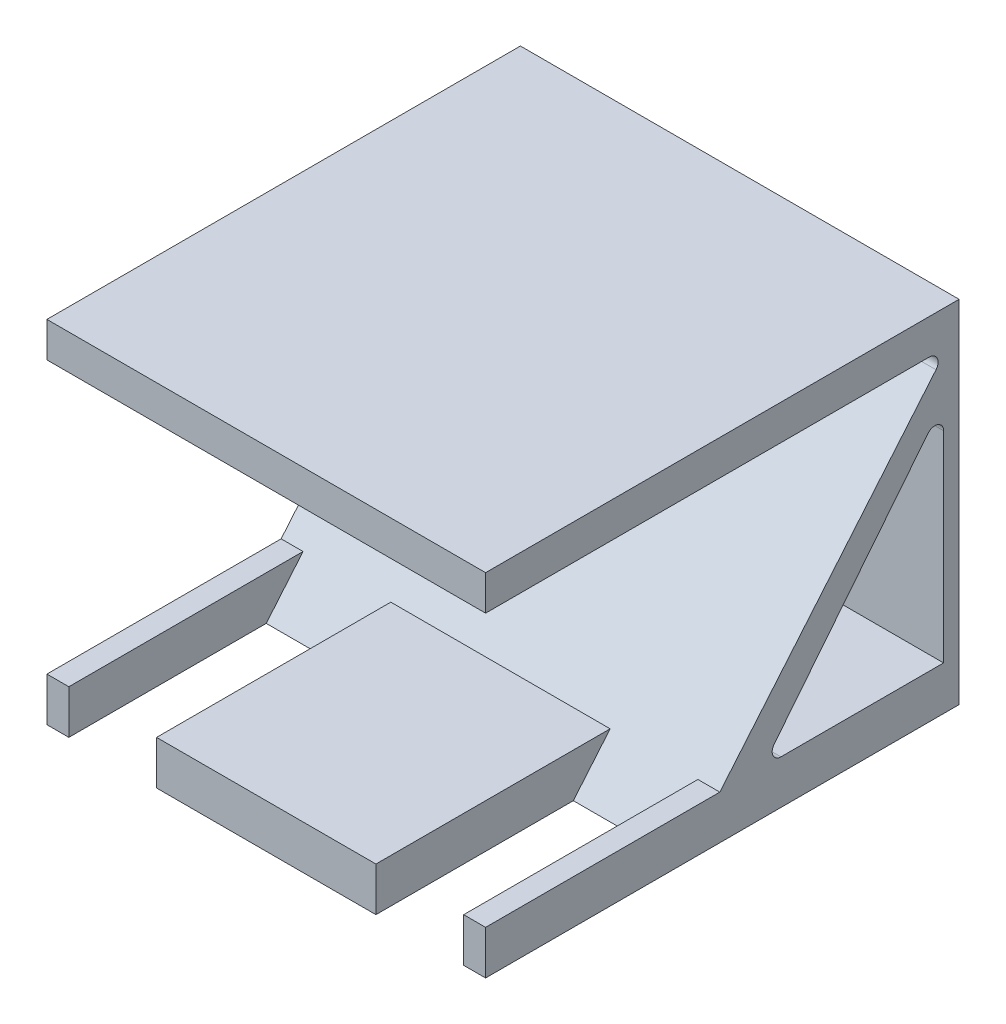
SolidWorks part; units mm, degrees
ref_plane "前视基准面" through (0, 0, 0) normal (0, 0, 1) x (1, 0, 0)
ref_plane "上视基准面" through (0, 0, 0) normal (0, 1, 0) x (1, 0, 0)
ref_plane "右视基准面" through (0, 0, 0) normal (1, 0, 0) x (0, 0, -1)
other "Configuration Table"
sketch "草图2" plane through (0, 0, 0) normal (0, 1, 0) x (1, 0, 0)
  line L0 (0, 45) -> (0, -64.4756) construction
  line L1 (-50, -45) -> (50, -45)
  line L2 (-50, -45) -> (-50, 45)
  line L3 (-50, 45) -> (50, 45)
  line L4 (50, -45) -> (50, 45)
  line L5 (-50, -45) -> (50, 45) construction
  line L6 (-50, 45) -> (50, -45) construction
  line L7 (-45, 45) -> (-25, 45)
  line L8 (-45, 45) -> (-45, -45)
  line L9 (-45, -45) -> (-25, -45)
  line L10 (-25, 45) -> (-25, -45)
  line L11 (45, -45) -> (25, -45)
  line L12 (25, 45) -> (25, -45)
  line L13 (45, 45) -> (25, 45)
  line L14 (45, 45) -> (45, -45)
  point P0 (0, 0)
  dimension "D1" = 100
  dimension "D2" = 90
  dimension "D3" = 20
  dimension "D4" = 5
extrude "凸台-拉伸1" add sketch "草图2" along normal blind 10 contours L8 L3 L2 L1 | L3 L14 L1 L4 | L12 L3 L10 L1
sketch "草图3" plane through (0, 0, 0) normal (1, 0, 0) x (0, 0, -1)
  line L0 (0, 0) -> (45, 0)
  line L2 (62.9325, 75) -> (0, 0)
  line L3 (-45, 0) -> (45, 0) construction
  line L4 (0, 0) -> (62.9325, 0)
  line L9 (62.9325, 0) -> (62.9325, 75)
  dimension "D1" = 130
  dimension "D2" = 75
extrude "凸台-拉伸5" add sketch "草图3" along normal mid plane 100 contours L4 L9 L2 L0
sketch "草图5" plane through (0, 0, 0) normal (1, 0, 0) x (0, 0, -1)
  line L0 (62.9325, 0) -> (62.9325, 75) construction
  line L1 (62.9325, 72.0181) -> (-45, 72.0181)
  line L2 (62.9325, 72.0181) -> (62.9325, 80.0181)
  line L3 (62.9325, 80.0181) -> (-45, 80.0181)
  line L4 (-45, 72.0181) -> (-45, 80.0181)
  dimension "D1" = 8
extrude "凸台-拉伸6" add sketch "草图5" along normal mid plane 100
sketch "草图6" plane through (0, 0, 0) normal (1, 0, 0) x (0, 0, -1)
  line L0 (18.1561, 10) -> (59.3985, 61.5268)
  line L1 (59.3985, 61.5268) -> (59.3985, 10)
  line L2 (59.3985, 10) -> (18.1561, 10)
extrude "切除-拉伸1" cut sketch "草图6" against normal through all both and the other way through all contours L2 L0 L1
fillet "圆角1" radius 2 2 edges at (0, 10, -18.1561) (0, 61.5268, -59.3985)
fillet "圆角2" radius 2 1 edges at (0, 72.0181, -60.4303)
